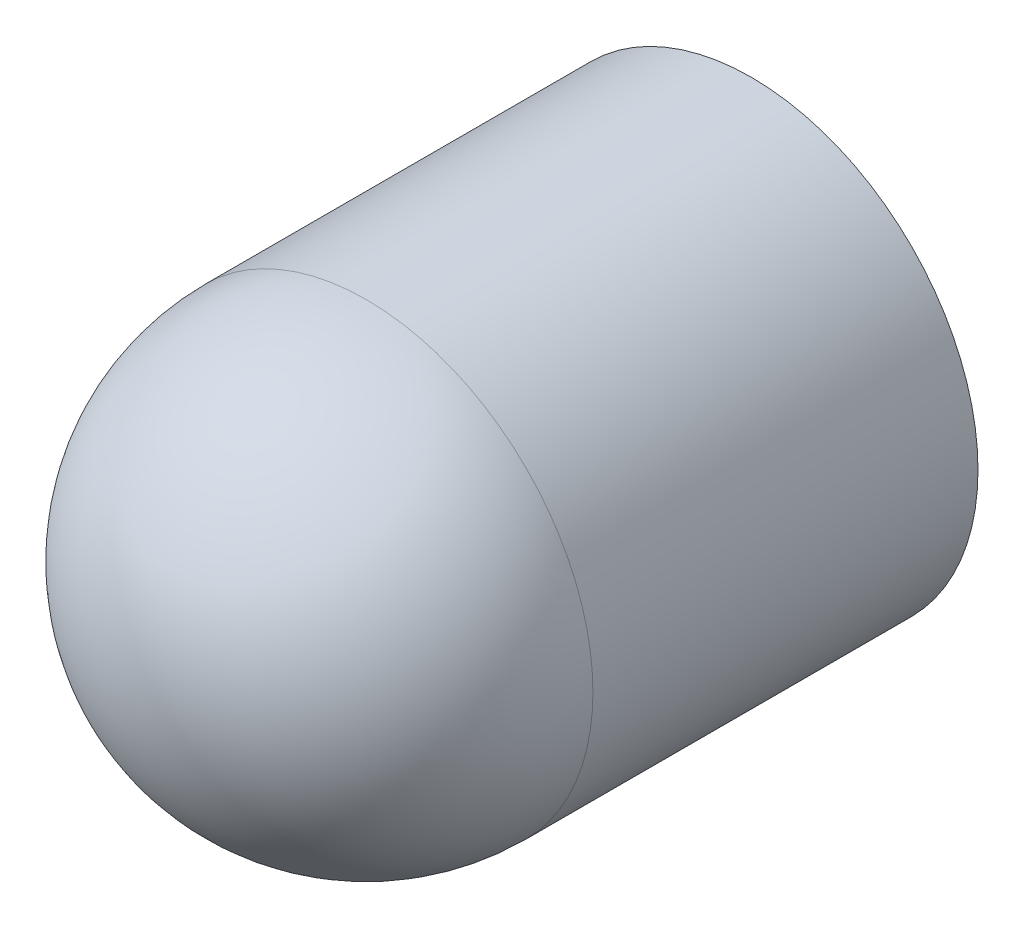
SolidWorks part; units mm, degrees
ref_plane "Front Plane" through (0, 0, 0) normal (0, 0, 1) x (1, 0, 0)
ref_plane "Top Plane" through (0, 0, 0) normal (0, 1, 0) x (1, 0, 0)
ref_plane "Right Plane" through (0, 0, 0) normal (1, 0, 0) x (0, 0, -1)
sketch "Sketch1" plane through (0, 0, 0) normal (0, 0, 1) x (1, 0, 0)
  line L0 (0, 1.2) -> (0, 1.25) construction
  circle A0 centre (0, 0) radius 1.25 construction
  circle A1 centre (0, 0) radius 1.2
  circle A2 centre (0, 0) radius 1.25 construction
  dimension "D1" = 0.05
extrude "Boss-Extrude1" add sketch "Sketch1" along normal up to surface (2.0389 mm away)
sketch "Sketch3" plane through (0, 0, 0) normal (0, 1, 0) x (1, 0, 0)
  line L0 (0, -2.0389) -> (0, -3.2389)
  line L1 (-1.2, -2.0389) -> (1.2, -2.0389) construction
  line L2 (0, -2.0389) -> (1.2, -2.0389)
  arc A0 (0, -3.2389) -> (1.2, -2.0389) centre (0, -2.0389) ccw
revolve "Revolve1" add sketch "Sketch3" angle 360 about L0
